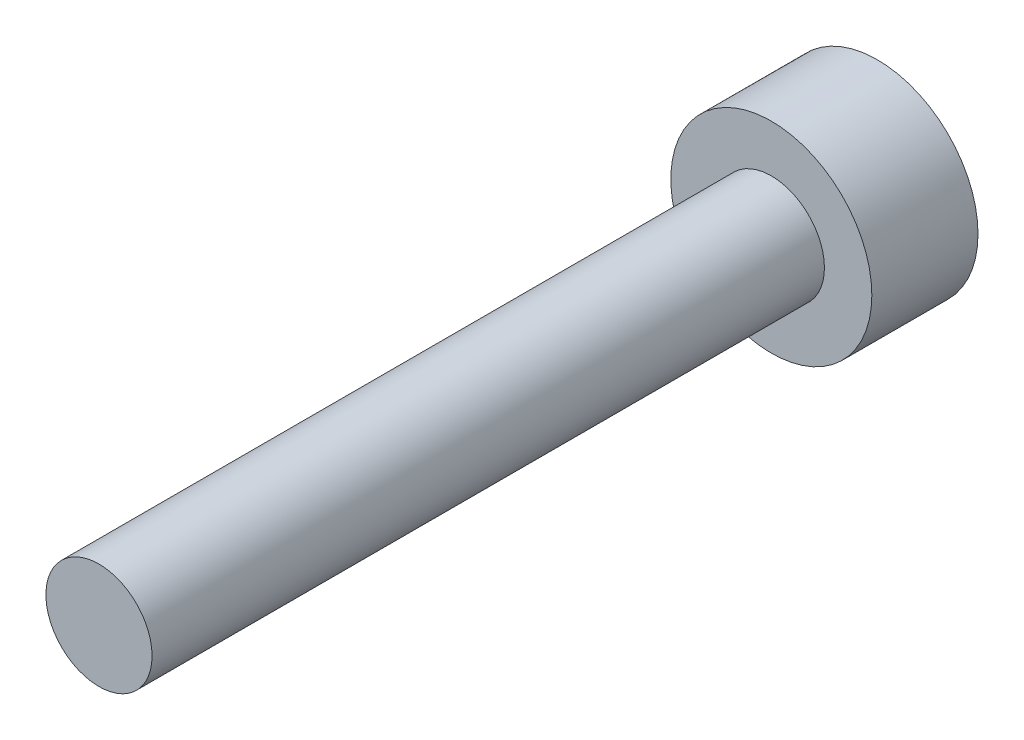
SolidWorks part; units mm, degrees
ref_plane "前视基准面" through (0, 0, 0) normal (0, 0, 1) x (1, 0, 0)
ref_plane "上视基准面" through (0, 0, 0) normal (0, 1, 0) x (1, 0, 0)
ref_plane "右视基准面" through (0, 0, 0) normal (1, 0, 0) x (0, 0, -1)
sketch "草图1" plane through (0, 0, 0) normal (0, 0, 1) x (1, 0, 0)
  circle A0 centre (0, 0) radius 2.84
extrude "凸台-拉伸1" add sketch "草图1" along normal blind 3
sketch "草图2" plane through (0, 0, 0) normal (0, 0, 1) x (1, 0, 0)
  circle A0 centre (0, 0) radius 1.5
extrude "凸台-拉伸2" add sketch "草图2" along normal blind 22
